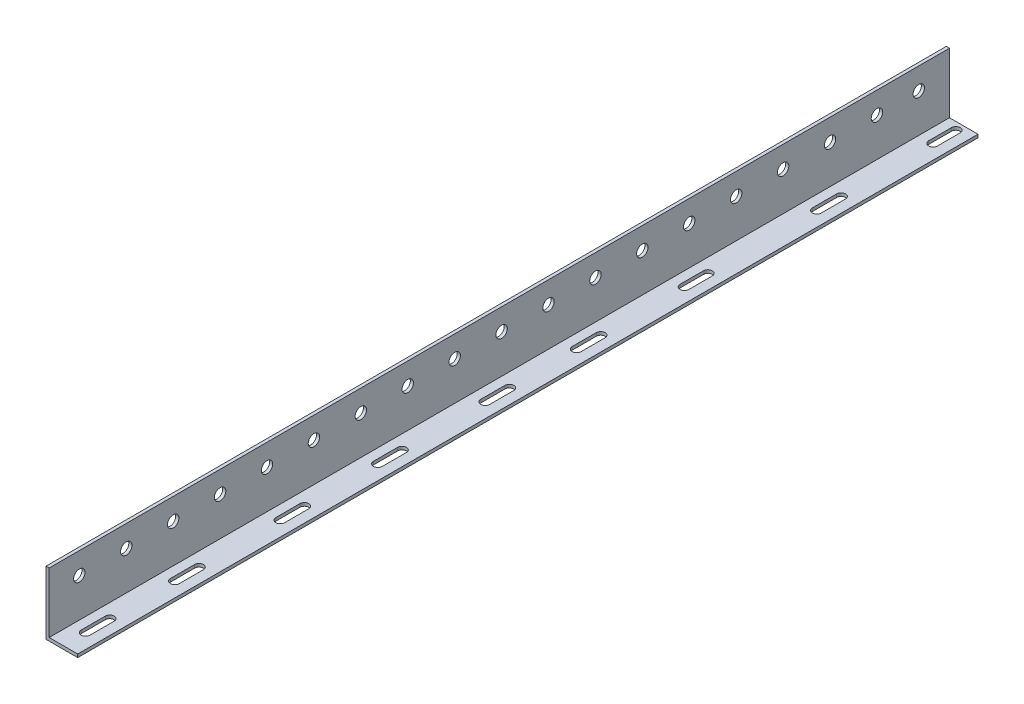
SolidWorks part; units mm, degrees
ref_plane "Front Plane" through (0, 0, 0) normal (0, 0, 1) x (1, 0, 0)
ref_plane "Top Plane" through (0, 0, 0) normal (0, 1, 0) x (1, 0, 0)
ref_plane "Right Plane" through (0, 0, 0) normal (1, 0, 0) x (0, 0, -1)
sketch "Sketch1" plane through (0, 0, 0) normal (0, 0, 1) x (1, 0, 0)
  line L0 (-9.4515, 23.8095) -> (-9.4515, -26.1905)
  line L1 (-9.4515, -26.1905) -> (15.5485, -26.1905)
  line L2 (15.5485, -26.1905) -> (15.5485, -23.6905)
  line L3 (15.5485, -23.6905) -> (-6.9515, -23.6905)
  line L4 (-6.9515, -23.6905) -> (-6.9515, 23.8095)
  line L5 (-6.9515, 23.8095) -> (-9.4515, 23.8095)
  dimension "D1" = 2.5
  dimension "D2" = 2.5
  dimension "D3" = 50
  dimension "D4" = 25
extrude "Boss-Extrude1" add sketch "Sketch1" along normal blind 710
sketch "Sketch2" plane through (-6.9515, 0, 0) normal (1, 0, 0) x (0, 0, -1)
  line L0 (-710.1981, 6.7245) -> (-0.1981, 6.665) construction
  circle A0 centre (-649.1981, 6.7194) radius 4.5
  circle A1 centre (-612.1981, 6.7163) radius 4.5
  circle A2 centre (-575.1981, 6.7132) radius 4.5
  circle A3 centre (-242.1981, 6.6853) radius 4.5
  circle A4 centre (-279.1981, 6.6884) radius 4.5
  circle A5 centre (-538.1981, 6.7101) radius 4.5
  circle A6 centre (-501.1981, 6.707) radius 4.5
  circle A7 centre (-464.1981, 6.7039) radius 4.5
  circle A8 centre (-427.1981, 6.7008) radius 4.5
  circle A9 centre (-390.1981, 6.6977) radius 4.5
  circle A10 centre (-353.1981, 6.6946) radius 4.5
  circle A11 centre (-316.1981, 6.6915) radius 4.5
  circle A12 centre (-686.1981, 6.7225) radius 4.5
  circle A13 centre (-24.1981, 6.667) radius 4.5
  circle A15 centre (-57.1981, 6.6698) radius 4.5
  circle A16 centre (-205.1981, 6.6822) radius 4.5
  circle A17 centre (-168.1981, 6.6791) radius 4.5
  circle A18 centre (-131.1981, 6.676) radius 4.5
  circle A19 centre (-94.1981, 6.6729) radius 4.5
  dimension "D12" = 37
  dimension "D13" = 24
  dimension "D15" = 37
  dimension "D16" = 37
  dimension "D20" = 37
  dimension "D21" = 33
  dimension "D2" = 37
  dimension "D3" = 37
  dimension "D4" = 37
  dimension "D5" = 37
  dimension "D6" = 37
  dimension "D7" = 37
  dimension "D8" = 37
  dimension "D9" = 37
  dimension "D10" = 37
  dimension "D11" = 37
  dimension "D14" = 24
  dimension "D17" = 37
  dimension "D18" = 37
  dimension "D19" = 37
sketch "Sketch3" plane through (0, -23.6905, 0) normal (0, 1, 0) x (1, 0, 0)
  line L0 (4.2985, -700.6581) -> (4.2985, 0) construction
  line L2 (15.5485, 0) -> (-6.9515, 0) construction
  line L8 (0.5711, -219.9284) -> (0.5711, -200.9284)
  line L9 (7.5711, -219.9284) -> (7.5711, -200.9284)
  line L12 (0.57, -115.4627) -> (0.5709, -96.4627)
  line L13 (7.5719, -115.4652) -> (7.5709, -96.4652)
  line L14 (0.5839, -24.0036) -> (0.5839, -6.0036)
  line L15 (7.5839, -24.0036) -> (7.5839, -6.0036)
  line L17 (0.5512, -304.9901) -> (0.5512, -285.9901)
  line L18 (7.5512, -304.9901) -> (7.5512, -285.9901)
  line L21 (0.5493, -377.0498) -> (0.5493, -358.0498)
  line L22 (7.5493, -377.0498) -> (7.5493, -358.0498)
  line L25 (0.5439, -461.6753) -> (0.5439, -442.6753)
  line L26 (7.5439, -461.6753) -> (7.5439, -442.6753)
  line L29 (0.482, -538.6402) -> (0.482, -519.6402)
  line L30 (7.482, -538.6402) -> (7.482, -519.6402)
  line L31 (0.5376, -621.7812) -> (0.5376, -602.7812)
  line L32 (7.5376, -621.7812) -> (7.5376, -602.7812)
  line L33 (0.5322, -692.1665) -> (0.5322, -673.1665)
  line L34 (7.5322, -692.1665) -> (7.5322, -673.1665)
  arc A6 (0.5711, -219.9284) -> (7.5711, -219.9284) centre (4.0711, -220.0094) ccw
  arc A7 (0.5711, -200.9284) -> (7.5711, -200.9284) centre (4.0711, -201.6353) cw
  arc A10 (0.57, -115.4627) -> (7.5719, -115.4652) centre (4.0709, -115.6067) ccw
  arc A11 (0.5709, -96.4627) -> (7.5709, -96.4652) centre (4.0709, -96.4639) cw
  arc A14 (0.5839, -6.0036) -> (7.5839, -6.0036) centre (4.0839, -6.0036) cw
  arc A15 (0.5839, -24.0036) -> (7.5839, -24.0036) centre (4.0839, -24.0036) ccw
  arc A16 (0.5512, -304.9901) -> (7.5512, -304.9901) centre (4.0512, -305.0711) ccw
  arc A17 (0.5512, -285.9901) -> (7.5512, -285.9901) centre (4.0512, -286.0388) cw
  arc A20 (0.5493, -377.0498) -> (7.5493, -377.0498) centre (4.0493, -377.1308) ccw
  arc A21 (0.5493, -358.0498) -> (7.5493, -358.0498) centre (4.0493, -358.0985) cw
  arc A24 (0.5439, -461.6753) -> (7.5439, -461.6753) centre (4.0439, -461.7563) ccw
  arc A25 (0.5439, -442.6753) -> (7.5439, -442.6753) centre (4.0439, -442.724) cw
  arc A28 (0.482, -538.6402) -> (7.482, -538.6402) centre (3.982, -538.7212) ccw
  arc A29 (0.482, -519.6402) -> (7.482, -519.6402) centre (3.982, -519.689) cw
  arc A30 (0.5376, -621.7812) -> (7.5376, -621.7812) centre (4.0376, -621.8622) ccw
  arc A31 (0.5376, -602.7812) -> (7.5376, -602.7812) centre (4.0376, -602.83) cw
  arc A32 (0.5322, -692.1665) -> (7.5322, -692.1665) centre (4.0322, -692.2475) ccw
  arc A33 (0.5322, -673.1665) -> (7.5322, -673.1665) centre (4.0322, -673.2152) cw
  dimension "D1" = 7
  dimension "D2" = 18
  dimension "D7" = 7
  dimension "D3" = 18
  dimension "D4" = 7
  dimension "D5" = 19
  dimension "D6" = 19
  dimension "D8" = 19
  dimension "D9" = 19
  dimension "D10" = 7
extrude "Cut-Extrude2" cut sketch "Sketch3" against normal blind 10
extrude "Cut-Extrude3" cut sketch "Sketch2" against normal blind 10
